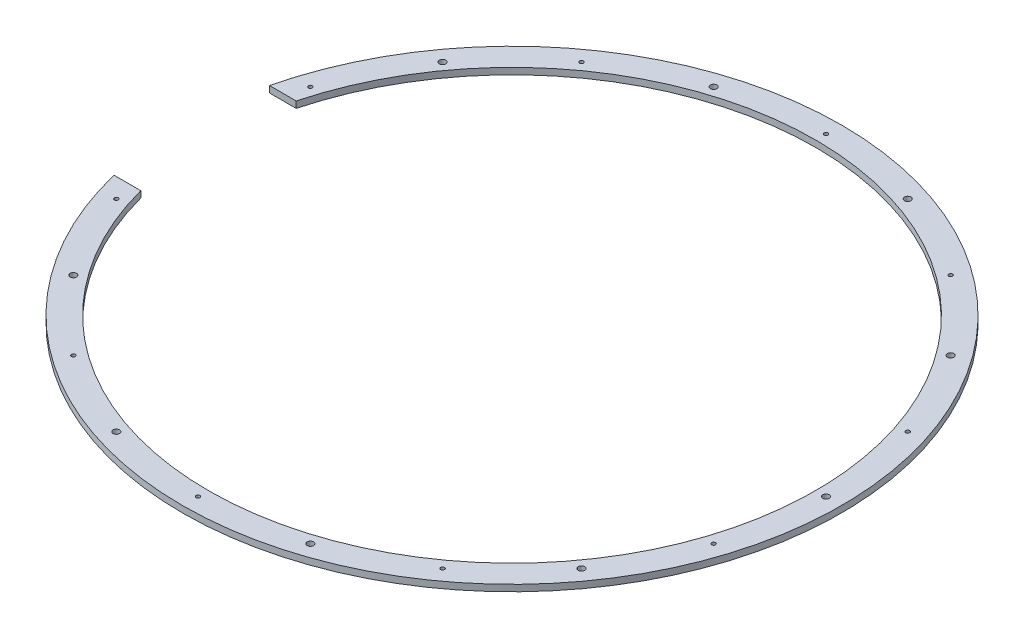
SolidWorks part; units mm, degrees
ref_plane "Front Plane" through (0, 0, 0) normal (0, 0, 1) x (1, 0, 0)
ref_plane "Top Plane" through (0, 0, 0) normal (0, 1, 0) x (1, 0, 0)
ref_plane "Right Plane" through (0, 0, 0) normal (1, 0, 0) x (0, 0, -1)
sketch "Sketch1" plane through (0, 0, 0) normal (0, 1, 0) x (1, 0, 0)
  circle A0 centre (0, 0) radius 254.5
  circle A1 centre (0, 0) radius 234.5
extrude "Boss-Extrude1" add sketch "Sketch1" along normal blind 5
sketch "Sketch2" plane through (0, 5, 0) normal (0, 1, 0) x (1, 0, 0)
  line L0 (-254.5, 0) -> (-226.6942, 0)
  line L1 (-226.6942, 0) -> (-226.6942, 60)
  line L2 (-226.6942, 60) -> (-254.5, 60)
  line L3 (-254.5, 60) -> (-254.5, 0)
  circle A0 centre (0, 0) radius 254.5 construction
  circle A1 centre (0, 0) radius 234.5 construction
  dimension "D1" = 60
extrude "Cut-Extrude1" cut sketch "Sketch2" against normal blind 5
mirror "Mirror1" about plane through (0, 0, 0) normal (0, 0, 1) of "Cut-Extrude1"
sketch "Sketch3" plane through (0, 5, 0) normal (0, 1, 0) x (1, 0, 0)
  circle A0 centre (242.5, 0) radius 2.5
  circle A1 centre (196.1866, -142.5379) radius 2.5
  circle A2 centre (74.9366, -230.6312) radius 2.5
  circle A3 centre (-74.9366, -230.6312) radius 2.5
  circle A4 centre (-196.1866, -142.5379) radius 2.5
  circle A5 centre (-242.5, 0) radius 2.5
  circle A6 centre (-196.1866, 142.5379) radius 2.5
  circle A7 centre (-74.9366, 230.6312) radius 2.5
  circle A8 centre (74.9366, 230.6312) radius 2.5
  circle A9 centre (196.1866, 142.5379) radius 2.5
  point P23 (0, 0)
  dimension "D1" = 242.5
  dimension "D2" = 10
extrude "Cut-Extrude2" cut sketch "Sketch3" against normal blind 5
sketch "Sketch4" plane through (0, 5, 0) normal (0, 1, 0) x (1, 0, 0)
  arc A0 (196.1866, 142.5379) -> (242.5, 0) centre (0, 0) cw
  circle A1 centre (230.6312, 74.9366) radius 1.5
  circle A2 centre (230.6312, -74.9366) radius 1.5
  circle A3 centre (142.5379, -196.1866) radius 1.5
  circle A4 centre (0, -242.5) radius 1.5
  circle A5 centre (-142.5379, -196.1866) radius 1.5
  circle A6 centre (-230.6312, -74.9366) radius 1.5
  circle A7 centre (-230.6312, 74.9366) radius 1.5
  circle A8 centre (-142.5379, 196.1866) radius 1.5
  circle A9 centre (0, 242.5) radius 1.5
  circle A10 centre (142.5379, 196.1866) radius 1.5
  circle A11 centre (230.6312, -74.9366) radius 1.5
  circle A12 centre (142.5379, -196.1866) radius 1.5
  circle A13 centre (0, -242.5) radius 1.5
  circle A14 centre (-142.5379, -196.1866) radius 1.5
  circle A15 centre (-230.6312, -74.9366) radius 1.5
  circle A16 centre (-230.6312, 74.9366) radius 1.5
  circle A17 centre (-142.5379, 196.1866) radius 1.5
  circle A18 centre (0, 242.5) radius 1.5
  circle A19 centre (142.5379, 196.1866) radius 1.5
  point P7 (0, 0)
  point P28 (0, 0)
  point P47 (0, 0)
  dimension "D1" = 10
  dimension "D2" = 10
extrude "Cut-Extrude3" cut sketch "Sketch4" against normal blind 5 contours A4 | A5 | A6 | A7 | A8 | A9 | A10 | A1 | A2 | A3
